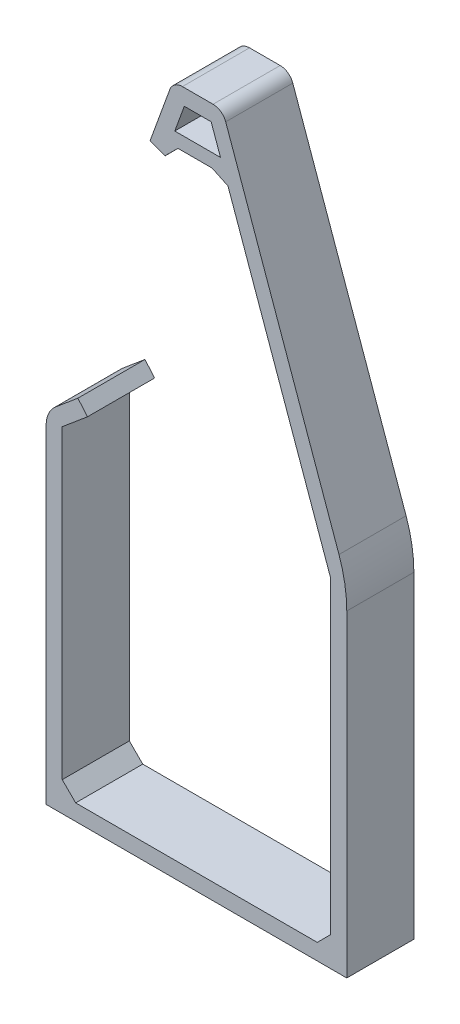
SolidWorks part; units mm, degrees
ref_plane "前视基准面" through (0, 0, 0) normal (0, 0, 1) x (1, 0, 0)
ref_plane "上视基准面" through (0, 0, 0) normal (0, 1, 0) x (1, 0, 0)
ref_plane "右视基准面" through (0, 0, 0) normal (1, 0, 0) x (0, 0, -1)
other "Configuration Table"
sketch "草图1" plane through (0, 0, 0) normal (0, 0, 1) x (1, 0, 0)
  line L0 (0, 0) -> (-100, 0)
  line L4 (-100, 0) -> (-100, 120)
  line L5 (0, 0) -> (0, 120)
  line L6 (-100, 120) -> (-54.5219, 245)
  line L8 (-44.5219, 245) -> (0, 120)
  line L9 (-54.5219, 245) -> (-44.5219, 245)
  point P4 (0, 120)
  point P8 (-100, 120)
  dimension "D1" = 125
  dimension "D2" = 100
  dimension "D3" = 120
  dimension "D4" = 120
  dimension "D5" = 10
  dimension "D6" = 132.6921
extrude "拉伸-薄壁1" add sketch "草图1" along normal blind 25 thin thin type one direction wall 6
sketch "草图2" plane through (-132.5043, 48.2084, 0) normal (-0.9397, 0.3419, 0) x (0, 0, 1)
  line L0 (25, 215.7962) -> (25, 77.5208) construction
  line L1 (0, 77.5208) -> (25, 77.5208)
  line L2 (0, 77.5208) -> (0, 190.7962)
  line L3 (0, 190.7962) -> (25, 190.7962)
  line L4 (25, 77.5208) -> (25, 190.7962)
  line L5 (25, 215.7962) -> (0, 215.7962) construction
  dimension "D1" = 25
extrude "切除-拉伸1" cut sketch "草图2" against normal blind 10
sketch "草图4" plane through (0, 0, 25) normal (0, 0, 1) x (1, 0, 0)
  line L5 (-58.0773, 235.2276) -> (-41.0412, 235.2276)
  line L6 (-54.5219, 245) -> (-61.6328, 225.4552) construction
  line L7 (0, 120) -> (-44.5219, 245) construction
  line L8 (-41.0412, 235.2276) -> (-39.2603, 230.2276)
  line L9 (-39.2603, 230.2276) -> (-59.8964, 230.2276)
  line L10 (-59.8964, 230.2276) -> (-58.0773, 235.2276)
  dimension "D1" = 5
extrude "凸台-拉伸1" add sketch "草图4" against normal up to surface (25 mm away) up to face at (-51.9258, 136.7093, 0)
fillet "圆角1" radius 50 1 edges at (6, 121.0366, 12.5)
fillet "圆角2" radius 5 2 edges at (-40.2897, 251, 12.5) (-58.7237, 251, 12.5)
chamfer "倒角1" distance 3 angle 45 2 edges at (-39.2603, 230.2276, 12.5) (-59.8964, 230.2276, 12.5)
sketch "草图5" plane through (0, 0, 25) normal (0, 0, 1) x (1, 0, 0)
  line L0 (-106, 121.0576) -> (-94.1634, 130.9923)
  line L1 (-94.1634, 130.9923) -> (-90.6086, 126.757)
  line L2 (-90.6086, 126.757) -> (-100, 118.8746)
  line L3 (-100, 118.8746) -> (-106, 121.0576) construction
  line L4 (-106, 121.0576) -> (-100, 118.8746)
  point P8 (-92.386, 128.8746)
  dimension "D1" = 60
  dimension "D2" = 10
extrude "凸台-拉伸2" add sketch "草图5" against normal up to surface (25 mm away) up to face at (-48.6374, 155.5176, 0)
fillet "圆角3" radius 10 1 edges at (-106, 121.0576, 12.5)
chamfer "倒角2" distance 5 angle 45 2 edges at (0, 0, 12.5) (-100, 0, 12.5)
